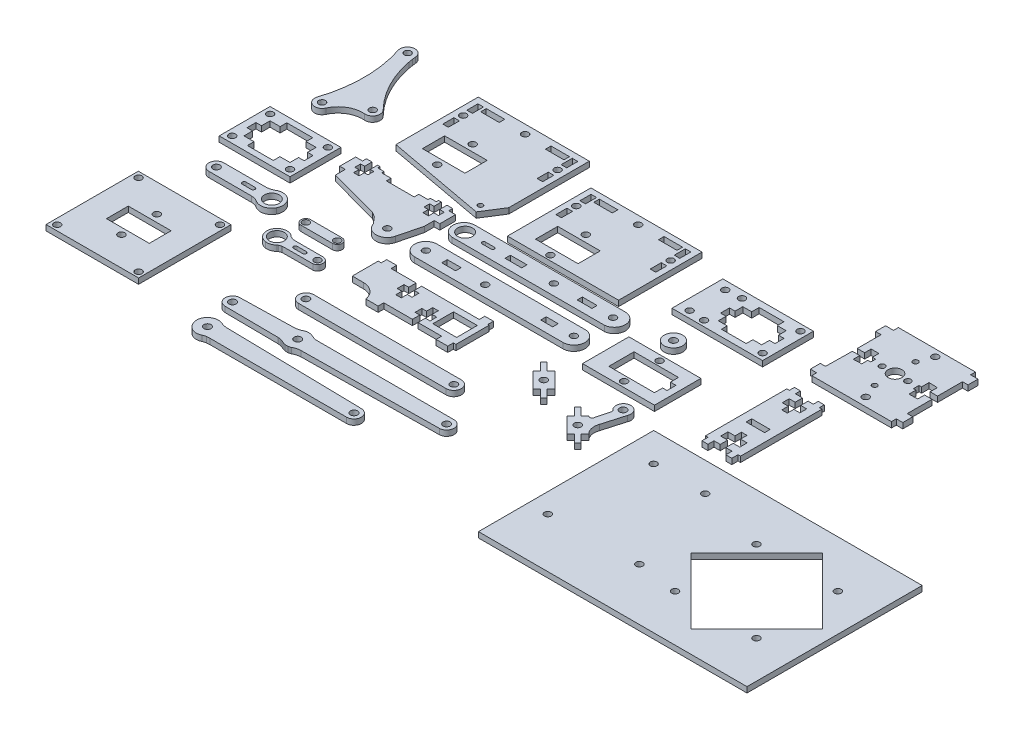
SolidWorks part; units mm, degrees
ref_plane "Front Plane" through (0, 0, 0) normal (0, 0, 1) x (1, 0, 0)
ref_plane "Top Plane" through (0, 0, 0) normal (0, 1, 0) x (1, 0, 0)
ref_plane "Right Plane" through (0, 0, 0) normal (1, 0, 0) x (0, 0, -1)
sketch "Sketch6" plane through (0, 0, -6.8736) normal (0, 1, 0) x (1, 0, 0)
  line L36 (172.3993, 17.524) -> (172.3993, 14.7799)
  line L37 (172.3993, 14.7799) -> (176.2794, 14.7799)
  line L38 (176.2794, 14.7799) -> (176.2794, 10.7799)
  line L39 (176.2794, 10.7799) -> (173.032, 10.7799)
  line L40 (173.032, 10.7799) -> (173.032, 7.063)
  line L41 (173.032, 7.063) -> (176.2794, 7.063)
  line L42 (176.2794, 7.063) -> (176.2794, 3.563)
  line L43 (176.2794, 3.563) -> (179.2794, 3.563)
  line L44 (179.2794, 3.563) -> (179.2794, 7.063)
  line L45 (179.2794, 7.063) -> (182.5439, 7.063)
  line L46 (182.5439, 7.063) -> (182.5439, 10.7799)
  line L47 (182.5439, 10.7799) -> (179.2794, 10.7799)
  line L48 (179.2794, 10.7799) -> (179.2794, 14.7799)
  line L49 (179.2794, 14.7799) -> (182.1277, 14.7799)
  line L50 (182.1277, 14.7799) -> (182.1277, 17.4216)
  line L54 (182.1277, -32.5784) -> (182.1277, -29.2201)
  line L55 (182.1277, -29.2201) -> (178.7635, -29.2201)
  line L56 (178.7635, -29.2201) -> (178.7635, -25.2201)
  line L57 (178.7635, -25.2201) -> (182.3404, -25.2201)
  line L58 (182.3404, -25.2201) -> (182.3404, -21.2526)
  line L59 (182.3404, -21.2526) -> (178.7635, -21.2526)
  line L60 (178.7635, -21.2526) -> (178.7635, -17.7526)
  line L61 (178.7635, -17.7526) -> (175.7635, -17.7526)
  line L62 (175.7635, -17.7526) -> (175.7635, -21.2526)
  line L63 (175.7635, -21.2526) -> (171.9828, -21.2526)
  line L64 (171.9828, -21.2526) -> (171.9828, -25.2201)
  line L65 (171.9828, -25.2201) -> (175.7635, -25.2201)
  line L66 (175.7635, -25.2201) -> (175.7635, -29.2201)
  line L67 (175.7635, -29.2201) -> (172.3993, -29.2201)
  line L68 (172.3993, -29.2201) -> (172.3993, -32.476)
  line L72 (172.2635, -8.7201) -> (182.2635, -8.7201)
  line L73 (182.2635, -8.7201) -> (182.2635, -11.7201)
  line L74 (182.2635, -11.7201) -> (172.2635, -11.7201)
  line L75 (172.2635, -11.7201) -> (172.2635, -8.7201)
  line L132 (186.7635, -29.2201) -> (185.3957, -29.2201)
  line L133 (185.3957, -29.2201) -> (185.3957, -32.5784)
  line L134 (167.7635, -29.2201) -> (169.1313, -29.2201)
  line L135 (169.1313, -29.2201) -> (169.1313, -32.476)
  line L136 (169.1313, 17.524) -> (169.1313, 14.7799)
  line L137 (169.1313, 14.7799) -> (167.7635, 14.7799)
  line L138 (185.3957, 17.4216) -> (185.3957, 14.7799)
  line L139 (185.3957, 14.7799) -> (186.7635, 14.7799)
  line L140 (167.7635, 14.7799) -> (167.7635, -29.2201)
  line L141 (169.1313, -32.476) -> (172.3993, -32.476)
  line L142 (182.1277, 17.4216) -> (185.3957, 17.4216)
  line L143 (186.7635, 14.7799) -> (186.7635, -29.2201)
  line L144 (185.3957, -32.5784) -> (182.1277, -32.5784)
  line L145 (169.1313, 17.524) -> (172.3993, 17.524)
  dimension "D6" = 1.3678
  dimension "D7" = 3.268
extrude "Boss-Extrude1" add sketch "Sketch6" along normal blind 3
sketch "Sketch12" plane through (0, 0, 0) normal (0, 1, 0) x (1, 0, 0)
  line L2 (6.7832, 13.9824) -> (88.1268, 13.9824)
  line L55 (6.1199, 2.1705) -> (88.7901, 2.1705)
  line L111 (69.455, 9.4201) -> (77.455, 9.4201)
  line L112 (69.455, 9.4201) -> (69.455, 6.6201)
  line L113 (69.455, 6.6201) -> (77.455, 6.6201)
  line L114 (77.455, 9.4201) -> (77.455, 6.6201)
  line L115 (30.455, 9.5201) -> (39.455, 9.5201)
  line L116 (30.455, 9.5201) -> (30.455, 6.6201)
  line L117 (30.455, 6.6201) -> (39.455, 6.6201)
  line L118 (39.455, 9.5201) -> (39.455, 6.6201)
  line L119 (17.455, 8.0462) -> (22.4277, 8.0462) construction
  line L120 (17.455, 8.9315) -> (22.4277, 8.9315)
  line L121 (17.455, 7.1609) -> (22.4277, 7.1609)
  arc A102 (6.7832, 13.9824) -> (6.1199, 2.1705) centre (6.7832, 8.0578) ccw
  arc A103 (88.1268, 13.9824) -> (88.7901, 2.1705) centre (88.1268, 8.0578) cw
  circle A104 centre (7.4627, 8.0462) radius 4
  circle A105 centre (87.455, 8.0201) radius 1.82
  circle A106 centre (55.455, 8.0201) radius 1.82
  arc A107 (17.455, 8.9315) -> (17.455, 7.1609) centre (17.455, 8.0462) ccw
  arc A108 (22.4277, 7.1609) -> (22.4277, 8.9315) centre (22.4277, 8.0462) ccw
  point P22 (19.9414, 8.0462)
  dimension "D1" = 3.64
  dimension "D3" = 3.64
  dimension "D4" = 8
extrude "Boss-Extrude3" add sketch "Sketch12" along normal blind 3 separate body
sketch "Sketch14" plane through (0, 0, 0) normal (0, 1, 0) x (1, 0, 0)
  line L0 (20.7129, 62.7973) -> (80.7867, 62.7973)
  line L1 (80.7867, 62.7973) -> (80.7867, 17.6847)
  line L2 (80.7867, 17.6847) -> (20.7129, 17.6847)
  line L3 (20.7129, 17.6847) -> (20.7129, 62.7973)
  line L4 (28.2425, 59.822) -> (38.2425, 59.822)
  line L5 (28.2425, 59.822) -> (28.2425, 56.822)
  line L6 (28.2425, 56.822) -> (38.2425, 56.822)
  line L7 (38.2425, 59.822) -> (38.2425, 56.822)
  line L8 (63.2425, 59.822) -> (73.2425, 59.822)
  line L9 (63.2425, 59.822) -> (63.2425, 56.822)
  line L10 (63.2425, 56.822) -> (73.2425, 56.822)
  line L11 (73.2425, 59.822) -> (73.2425, 56.822)
  line L12 (74.7425, 59.822) -> (77.7425, 59.822)
  line L13 (74.7425, 59.822) -> (74.7425, 53.822)
  line L14 (74.7425, 53.822) -> (77.7425, 53.822)
  line L15 (77.7425, 59.822) -> (77.7425, 53.822)
  line L16 (74.7425, 46.822) -> (77.7425, 46.822)
  line L17 (74.7425, 46.822) -> (74.7425, 40.822)
  line L18 (74.7425, 40.822) -> (77.7425, 40.822)
  line L19 (77.7425, 46.822) -> (77.7425, 40.822)
  line L20 (29.7425, 35.822) -> (52.7425, 35.822)
  line L21 (29.7425, 35.822) -> (29.7425, 23.822)
  line L22 (29.7425, 23.822) -> (52.7425, 23.822)
  line L23 (52.7425, 35.822) -> (52.7425, 23.822)
  line L24 (23.7425, 46.822) -> (26.7425, 46.822)
  line L25 (23.7425, 46.822) -> (23.7425, 40.822)
  line L26 (23.7425, 40.822) -> (26.7425, 40.822)
  line L27 (26.7425, 46.822) -> (26.7425, 40.822)
  line L28 (23.7425, 59.822) -> (26.7425, 59.822)
  line L29 (23.7425, 59.822) -> (23.7425, 53.822)
  line L30 (23.7425, 53.822) -> (26.7425, 53.822)
  line L31 (26.7425, 59.822) -> (26.7425, 53.822)
  circle A0 centre (50.7425, 58.322) radius 1.82
  circle A1 centre (41.2425, 39.4969) radius 1.82
  circle A2 centre (41.2425, 20.3569) radius 1.82
  circle A3 centre (76.2425, 50.322) radius 1.82
  circle A4 centre (25.2425, 50.322) radius 1.82
  dimension "D1" = 19.14
  dimension "D2" = 3.64
  dimension "D3" = 3.64
  dimension "D4" = 3.64
  dimension "D5" = 3.64
extrude "Boss-Extrude4" add sketch "Sketch14" along normal blind 3 separate body
sketch "Sketch18" plane through (0, 0, 0) normal (0, 1, 0) x (1, 0, 0)
  line L0 (-52.2788, 74.8705) -> (7.7767, 74.8705)
  line L1 (7.7767, 74.8705) -> (7.7767, 31.3788)
  line L2 (7.7767, 31.3788) -> (0.9291, 20.5522)
  line L3 (0.9291, 20.5522) -> (-52.2788, 30.361)
  line L4 (-52.2788, 30.361) -> (-52.2788, 74.8705)
  line L5 (-44.7078, 71.6303) -> (-34.7078, 71.6303)
  line L6 (-44.7078, 71.6303) -> (-44.7078, 68.6303)
  line L7 (-44.7078, 68.6303) -> (-34.7078, 68.6303)
  line L8 (-34.7078, 71.6303) -> (-34.7078, 68.6303)
  line L9 (-49.2078, 71.6303) -> (-46.2078, 71.6303)
  line L10 (-49.2078, 71.6303) -> (-49.2078, 65.6303)
  line L11 (-49.2078, 65.6303) -> (-46.2078, 65.6303)
  line L12 (-46.2078, 71.6303) -> (-46.2078, 65.6303)
  line L13 (-49.2078, 58.6303) -> (-46.2078, 58.6303)
  line L14 (-49.2078, 58.6303) -> (-49.2078, 52.6303)
  line L15 (-49.2078, 52.6303) -> (-46.2078, 52.6303)
  line L16 (-46.2078, 58.6303) -> (-46.2078, 52.6303)
  line L17 (-43.2078, 47.6303) -> (-20.2078, 47.6303)
  line L18 (-43.2078, 47.6303) -> (-43.2078, 35.6303)
  line L19 (-43.2078, 35.6303) -> (-20.2078, 35.6303)
  line L20 (-20.2078, 47.6303) -> (-20.2078, 35.6303)
  line L21 (-9.7078, 71.6303) -> (0.2922, 71.6303)
  line L22 (-9.7078, 71.6303) -> (-9.7078, 68.6303)
  line L23 (-9.7078, 68.6303) -> (0.2922, 68.6303)
  line L24 (0.2922, 71.6303) -> (0.2922, 68.6303)
  line L25 (1.7922, 71.6303) -> (4.7922, 71.6303)
  line L26 (1.7922, 71.6303) -> (1.7922, 65.6303)
  line L27 (1.7922, 65.6303) -> (4.7922, 65.6303)
  line L28 (4.7922, 71.6303) -> (4.7922, 65.6303)
  line L29 (1.7922, 58.6303) -> (4.7922, 58.6303)
  line L30 (1.7922, 58.6303) -> (1.7922, 52.6303)
  line L31 (1.7922, 52.6303) -> (4.7922, 52.6303)
  line L32 (4.7922, 58.6303) -> (4.7922, 52.6303)
  circle A0 centre (3.3054, 62.1514) radius 1.82
  circle A1 centre (-0.9558, 24.7244) radius 1.2998
  circle A2 centre (-31.7081, 32.1289) radius 1.82
  circle A3 centre (-31.6898, 51.2689) radius 1.82
  circle A4 centre (-47.7078, 62.1303) radius 1.82
  circle A5 centre (-22.2078, 70.1303) radius 1.82
  dimension "D1" = 3.64
  dimension "D2" = 19.14
sketch "Sketch20" plane through (0, 0, 0) normal (0, 1, 0) x (1, 0, 0)
  line L0 (-3.3445, 5.1376) -> (-6.3445, 5.1376)
  line L1 (-6.3445, -0.1855) -> (-9.5309, -12.7114)
  line L2 (-21.2346, -12.8672) -> (-24.3389, -9.2481)
  line L3 (-24.3389, -9.2481) -> (-27.0786, -7.6072)
  line L4 (-27.0786, -7.6072) -> (-54.3445, -0.2275)
  line L5 (-54.3445, -0.2275) -> (-54.3445, 5.0581)
  line L6 (-54.3445, 5.0581) -> (-57.3445, 5.0581)
  line L7 (-57.3445, 5.0581) -> (-57.3445, 13.6523)
  line L8 (-57.3445, 13.6523) -> (-53.6006, 13.6523)
  line L9 (-53.6006, 13.6523) -> (-53.6006, 15.7725)
  line L10 (-53.6006, 15.7725) -> (-50.5945, 15.7725)
  line L11 (-50.5945, 15.7725) -> (-50.5945, 11.7725)
  line L12 (-50.5945, 11.7725) -> (-52.7659, 11.7725)
  line L13 (-52.7659, 11.7725) -> (-52.7659, 8.6302)
  line L14 (-52.7659, 8.6302) -> (-50.5945, 8.6302)
  line L15 (-50.5945, 8.6302) -> (-50.5945, 5.7725)
  line L16 (-50.5945, 5.7725) -> (-47.5945, 5.7725)
  line L17 (-47.5945, 5.7725) -> (-47.5945, 8.6302)
  line L18 (-47.5945, 8.6302) -> (-45.6767, 8.6302)
  line L19 (-45.6767, 8.6302) -> (-45.6767, 11.7725)
  line L20 (-45.6767, 11.7725) -> (-47.5945, 11.7725)
  line L21 (-47.5945, 11.7725) -> (-47.5945, 15.7725)
  line L22 (-47.5945, 15.7725) -> (-46.26, 15.7725)
  line L23 (-46.26, 15.7725) -> (-46.26, 14.5225)
  line L24 (-46.26, 14.5225) -> (-42.8445, 14.5225)
  line L25 (-42.8445, 14.5225) -> (-42.8445, 13.2725)
  line L26 (-42.8445, 13.2725) -> (-37.8445, 13.2725)
  line L27 (-37.8445, 13.2725) -> (-37.8445, 10.7725)
  line L28 (-37.8445, 10.7725) -> (-22.8445, 10.7725)
  line L29 (-22.8445, 10.7725) -> (-22.8445, 13.2725)
  line L30 (-22.8445, 13.2725) -> (-17.8445, 13.2725)
  line L31 (-17.8445, 13.2725) -> (-17.8445, 14.5225)
  line L32 (-17.8445, 14.5225) -> (-14.6403, 14.5225)
  line L33 (-14.6403, 14.5225) -> (-14.6403, 15.7725)
  line L34 (-14.6403, 15.7725) -> (-13.0945, 15.7725)
  line L35 (-13.0945, 15.7725) -> (-13.0945, 11.7725)
  line L36 (-13.0945, 11.7725) -> (-15.4488, 11.7725)
  line L37 (-15.4488, 11.7725) -> (-15.4488, 8.6851)
  line L38 (-15.4488, 8.6851) -> (-13.0945, 8.6851)
  line L39 (-13.0945, 8.6851) -> (-13.0945, 5.7725)
  line L40 (-13.0945, 5.7725) -> (-10.0945, 5.7725)
  line L41 (-10.0945, 5.7725) -> (-10.0945, 8.6674)
  line L42 (-10.0945, 8.6674) -> (-7.5507, 8.6674)
  line L43 (-7.5507, 8.6674) -> (-7.5507, 11.7725)
  line L44 (-7.5507, 11.7725) -> (-10.0945, 11.7725)
  line L45 (-10.0945, 11.7725) -> (-10.0945, 15.7725)
  line L46 (-10.0945, 15.7725) -> (-7.0098, 15.7725)
  line L47 (-7.0098, 15.7725) -> (-7.0098, 13.684)
  line L48 (-7.0098, 13.684) -> (-3.3445, 13.6514)
  line L49 (-3.3445, 13.6514) -> (-3.3445, 5.1376)
  line L50 (-6.3445, 5.1376) -> (-6.3445, -0.1855)
  arc A0 (-9.5309, -12.7114) -> (-21.2346, -12.8672) centre (-15.4037, -11.2174) cw
  circle A1 centre (-15.3445, -11.2275) radius 1.82
  dimension "D1" = 3.64
sketch "Sketch22" plane through (0, 0, 0) normal (0, 1, 0) x (1, 0, 0)
  line L0 (-22.8304, -83.5062) -> (5.98, -82.8529)
  line L1 (18.5125, -82.749) -> (92.2578, -82.749)
  line L2 (92.3104, -90.7487) -> (18.5715, -91.7184)
  line L3 (6.0387, -91.7793) -> (-22.7778, -91.5049)
  arc A0 (5.98, -82.8529) -> (10.0623, -81.6918) centre (5.7889, -74.4239) ccw
  arc A1 (10.0623, -81.6918) -> (10.658, -81.4927) centre (10.8295, -82.9967) cw
  arc A2 (10.658, -81.4927) -> (11.2714, -81.3569) centre (10.3161, -78.495) ccw
  arc A3 (11.2714, -81.3569) -> (11.8955, -81.2861) centre (11.7502, -82.7912) cw
  arc A4 (11.8955, -81.2861) -> (12.5237, -81.2808) centre (12.1844, -78.2942) ccw
  arc A5 (12.5237, -81.2808) -> (13.1489, -81.3413) centre (12.6941, -82.7806) cw
  arc A6 (13.1489, -81.3413) -> (13.7644, -81.4668) centre (14.0525, -78.4818) ccw
  arc A7 (13.7644, -81.4668) -> (14.3634, -81.656) centre (13.6195, -82.9685) cw
  arc A8 (14.3634, -81.656) -> (14.9394, -81.9067) centre (15.8391, -79.0526) ccw
  arc A9 (14.9394, -81.9067) -> (15.6165, -82.2065) centre (13.9387, -85.0813) cw
  arc A10 (15.6165, -82.2065) -> (16.3185, -82.4423) centre (16.5367, -80.6298) ccw
  arc A11 (16.3185, -82.4423) -> (17.0393, -82.6122) centre (15.9213, -85.7415) cw
  arc A12 (17.0393, -82.6122) -> (17.7727, -82.7147) centre (17.6534, -80.8935) ccw
  arc A13 (17.7727, -82.7147) -> (18.5125, -82.749) centre (17.9898, -86.0281) cw
  arc A14 (92.2578, -82.749) -> (92.3104, -90.7487) centre (92.2578, -86.7491) cw
  arc A15 (18.5715, -91.7184) -> (14.4371, -92.8659) centre (18.6822, -100.1392) ccw
  arc A16 (14.4371, -92.8659) -> (13.8407, -93.0629) centre (13.6751, -91.5605) cw
  arc A17 (13.8407, -93.0629) -> (13.2269, -93.1965) centre (14.1702, -96.0538) ccw
  arc A18 (13.2269, -93.1965) -> (12.6025, -93.2652) centre (12.753, -91.7611) cw
  arc A19 (12.6025, -93.2652) -> (11.9743, -93.2682) centre (12.3027, -96.2616) ccw
  arc A20 (11.9743, -93.2682) -> (11.3493, -93.2055) centre (11.8094, -91.7654) cw
  arc A21 (11.3493, -93.2055) -> (10.7342, -93.0779) centre (10.4346, -96.0685) ccw
  arc A22 (10.7342, -93.0779) -> (10.1359, -92.8866) centre (10.8846, -91.5762) cw
  arc A23 (10.1359, -92.8866) -> (9.5608, -92.6338) centre (8.6482, -95.4904) ccw
  arc A24 (9.5608, -92.6338) -> (8.8936, -92.3352) centre (10.5595, -89.5075) cw
  arc A25 (8.8936, -92.3352) -> (8.202, -92.0988) centre (7.9736, -93.8967) ccw
  arc A26 (8.202, -92.0988) -> (7.4916, -91.9264) centre (8.615, -88.8472) cw
  arc A27 (7.4916, -91.9264) -> (6.7685, -91.8196) centre (6.8709, -93.6279) ccw
  arc A28 (6.7685, -91.8196) -> (6.0387, -91.7793) centre (6.5832, -88.5467) cw
  arc A29 (-22.7778, -91.5049) -> (-22.8304, -83.5062) centre (-22.7397, -87.5052) cw
  circle A30 centre (-22.7398, -87.5051) radius 1.925
  circle A31 centre (12.2595, -87.275) radius 1.925
  circle A32 centre (92.2578, -86.749) radius 1.925
  dimension "D1" = 3.85
  dimension "D2" = 3.85
sketch "Sketch23" plane through (0, 0, 0) normal (0, 1, 0) x (1, 0, 0)
  line L0 (62.0938, -102.6123) -> (-12.185, -101.1529)
  line L1 (62.0145, -110.6115) -> (-11.7091, -110.5993)
  arc A0 (-18.7722, -99.8781) -> (-23.9525, -106.2408) centre (-18.181, -105.6496) ccw
  arc A1 (-23.9525, -106.2408) -> (-20.8301, -111.1061) centre (-17.5842, -105.5884) ccw
  arc A2 (-20.8301, -111.1061) -> (-15.5368, -111.3053) centre (-17.9986, -106.2928) ccw
  arc A3 (-15.5368, -111.3053) -> (-13.6142, -110.7239) centre (-12.8064, -116.8649) cw
  arc A4 (-13.6142, -110.7239) -> (-11.7091, -110.5993) centre (-11.7115, -125.1879) cw
  arc A5 (-18.7722, -99.8781) -> (-14.8108, -100.6548) centre (-18.0664, -106.7687) cw
  arc A6 (-14.8108, -100.6548) -> (-13.5188, -101.0143) centre (-13.353, -97.9172) ccw
  arc A7 (-13.5188, -101.0143) -> (-12.185, -101.1529) centre (-14.2348, -114.3916) cw
  arc A8 (62.0938, -102.6123) -> (62.0145, -110.6115) centre (62.0152, -106.6115) cw
  circle A9 centre (62.0152, -106.6115) radius 1.925
  circle A10 centre (-17.9809, -105.8257) radius 1.925
  dimension "D1" = 3.85
  dimension "D2" = 3.85
sketch "Sketch24" plane through (0, 0, 0) normal (0, 1, 0) x (1, 0, 0)
  line L0 (-90.2893, -24.7085) -> (-67.8284, -24.7085)
  line L1 (-90.2954, -32.7085) -> (-67.194, -32.744)
  line L2 (-75.2787, -28.7329) -> (-70.3703, -28.7329) construction
  line L3 (-75.2787, -27.7198) -> (-70.3703, -27.7198)
  line L4 (-75.2787, -29.7461) -> (-70.3703, -29.7461)
  arc A0 (-67.8284, -24.7085) -> (-62.5705, -23.1591) centre (-67.8284, -15.0125) ccw
  arc A1 (-62.5705, -23.1591) -> (-54.9836, -31.523) centre (-60.3229, -28.7434) cw
  arc A2 (-54.9836, -31.523) -> (-63.9473, -33.5823) centre (-60.343, -28.7329) cw
  arc A3 (-67.194, -32.744) -> (-63.9473, -33.5823) centre (-67.2043, -39.4905) cw
  arc A4 (-75.2787, -27.7198) -> (-75.2787, -29.7461) centre (-75.2787, -28.7329) ccw
  arc A5 (-70.3703, -29.7461) -> (-70.3703, -27.7198) centre (-70.3703, -28.7329) ccw
  circle A6 centre (-90.2893, -28.7085) radius 1.925
  circle A7 centre (-60.2893, -28.7085) radius 4
  arc A8 (-90.2954, -32.7085) -> (-90.2893, -24.7085) centre (-90.2893, -28.7085) cw
  point P13 (-72.8245, -28.7329)
  dimension "D1" = 3.85
  dimension "D2" = 8
sketch "Sketch26" plane through (0, 0, 0) normal (0, 1, 0) x (1, 0, 0)
  line L0 (-87.7528, 74.718) -> (-87.4104, 72.6313)
  line L1 (-87.7528, 74.718) -> (-88.0164, 76.816)
  arc A0 (-88.0164, 76.816) -> (-95.8236, 75.1147) centre (-92.0067, 76.3629) ccw
  arc A1 (-95.8236, 75.1147) -> (-95.7872, 31.4073) centre (-162.8228, 53.2052) cw
  arc A2 (-95.7872, 31.4073) -> (-88.3346, 28.5226) centre (-91.9816, 30.1698) ccw
  arc A3 (-88.3346, 28.5226) -> (-75.123, 36.3095) centre (-76.205, 23.044) cw
  arc A4 (-75.123, 36.3095) -> (-71.9331, 43.1193) centre (-74.7969, 40.3087) ccw
  arc A5 (-71.9331, 43.1193) -> (-87.4104, 72.6313) centre (-30.7636, 83.5248) cw
  circle A6 centre (-74.764, 40.2933) radius 1.82
  circle A7 centre (-91.9939, 30.1381) radius 1.82
  circle A8 centre (-91.9939, 76.3923) radius 1.82
  dimension "D1" = 3.64
  dimension "D2" = 3.64
  dimension "D3" = 3.64
sketch "Sketch27" plane through (0, 0, 0) normal (0, 1, 0) x (1, 0, 0)
  line L0 (-91.9831, 11.0737) -> (-77.9831, 11.0737)
  line L1 (-104.1231, 14.1616) -> (-65.8431, 14.1616)
  line L2 (-104.1231, 14.1616) -> (-104.1231, -13.3284)
  line L3 (-104.1231, -13.3284) -> (-65.8431, -13.3284)
  line L4 (-65.8431, 14.1616) -> (-65.8431, -13.3284)
  line L5 (-77.9831, 11.0737) -> (-77.9831, 7.4737)
  line L6 (-77.9831, 7.4737) -> (-72.5331, 7.4737)
  line L7 (-72.5331, 7.4737) -> (-72.5331, 2.8437)
  line L8 (-69.5331, 2.8437) -> (-69.5331, -2.0063)
  line L9 (-69.5331, -2.0063) -> (-72.5331, -2.0063)
  line L10 (-72.5331, -2.0063) -> (-72.5331, -6.6363)
  line L11 (-72.5331, -6.6363) -> (-77.9831, -6.6363)
  line L12 (-77.9831, -6.6363) -> (-77.9831, -10.2363)
  line L13 (-77.9831, -10.2363) -> (-91.9831, -10.2363)
  line L14 (-91.9831, -10.2363) -> (-91.9831, -6.6384)
  line L15 (-91.9831, -6.6384) -> (-97.4331, -6.6384)
  line L16 (-97.4331, -6.6384) -> (-97.4331, -2.0084)
  line L17 (-97.4331, -2.0084) -> (-100.4331, -2.0084)
  line L18 (-100.4331, -2.0084) -> (-100.4331, 2.8416)
  line L19 (-100.4331, 2.8416) -> (-97.4331, 2.8416)
  line L20 (-97.4331, 2.8416) -> (-97.4331, 7.4716)
  line L21 (-97.4331, 7.4716) -> (-91.9831, 7.4716)
  line L22 (-91.9831, 7.4716) -> (-91.9831, 11.0737)
  line L23 (-72.5331, 2.8437) -> (-69.5331, 2.8437)
  circle A0 centre (-100.6231, 10.6616) radius 1.82
  circle A1 centre (-100.6231, -9.8284) radius 1.82
  circle A2 centre (-69.3431, -9.8263) radius 1.82
  circle A3 centre (-69.3431, 10.6616) radius 1.82
  dimension "D1" = 3.64
  dimension "D2" = 14
  dimension "D3" = 3.6
  dimension "D4" = 3.6
  dimension "D5" = 4.85
  dimension "D6" = 4.63
  dimension "D7" = 3.19
  dimension "D8" = 3.19
  dimension "D9" = 3.19
  dimension "D10" = 5.45
  dimension "D11" = 3
  dimension "D12" = 3.19
  dimension "D13" = 3.19
  dimension "D14" = 3.19
  dimension "D15" = 3.5
  dimension "D16" = 3.5
  dimension "D17" = 3.5
sketch "Sketch28" plane through (0, 0, 0) normal (0, 1, 0) x (1, 0, 0)
  line L0 (109.0997, -2.2732) -> (133.1497, -2.2732)
  line L1 (100.7124, 3.3321) -> (139.6281, 3.3321)
  line L2 (100.7124, 3.3321) -> (100.7124, -21.7433)
  line L3 (100.7124, -21.7433) -> (139.6281, -21.7433)
  line L4 (139.6281, 3.3321) -> (139.6281, -21.7433)
  line L5 (133.1497, -2.2732) -> (133.1497, -6.6732)
  line L6 (133.1497, -6.6732) -> (136.1497, -6.6732)
  line L7 (136.1497, -6.6732) -> (136.1497, -11.5232)
  line L8 (136.1497, -11.5232) -> (133.7949, -11.5232)
  line L9 (133.7949, -11.5232) -> (133.7949, -15.9232)
  line L10 (133.7949, -15.9232) -> (109.0997, -15.9232)
  line L11 (109.0997, -15.9232) -> (109.0997, -2.2732)
  circle A0 centre (120.2396, 0.384) radius 1.82
  circle A1 centre (120.2396, -18.756) radius 1.82
  dimension "D1" = 3.64
  dimension "D2" = 3.64
  dimension "D3" = 3
  dimension "D4" = 24.05
  dimension "D5" = 4.85
  dimension "D6" = 4.4
  dimension "D7" = 19.14
sketch "Sketch29" plane through (0, 0, 0) normal (0, 1, 0) x (1, 0, 0)
  line L0 (122.1756, 52.3026) -> (135.5756, 52.3026)
  line L1 (98.979, 55.8405) -> (147.9656, 55.8405)
  line L2 (98.979, 55.8405) -> (98.979, 28.3505)
  line L3 (98.979, 28.3505) -> (147.9656, 28.3505)
  line L4 (147.9656, 55.8405) -> (147.9656, 28.3505)
  line L5 (135.5756, 52.3026) -> (135.5756, 48.7026)
  line L6 (135.5756, 48.7026) -> (140.3756, 48.7026)
  line L7 (140.3756, 48.7026) -> (140.3756, 44.5226)
  line L8 (143.3756, 44.5226) -> (143.3756, 39.6726)
  line L9 (143.3756, 39.6726) -> (140.3756, 39.6726)
  line L10 (140.3756, 39.6726) -> (140.3756, 35.4926)
  line L11 (140.3756, 35.4926) -> (135.5756, 35.4926)
  line L12 (135.5756, 35.4926) -> (135.5756, 31.8926)
  line L13 (135.5756, 31.8926) -> (122.1756, 31.8926)
  line L14 (122.1756, 31.8926) -> (122.1756, 35.0385)
  line L15 (122.1756, 35.0385) -> (117.3756, 35.0385)
  line L16 (117.3756, 35.0385) -> (117.3756, 39.2185)
  line L17 (117.3756, 39.2185) -> (114.3756, 39.2185)
  line L18 (114.3756, 39.2185) -> (114.3756, 44.0726)
  line L19 (114.3756, 44.0726) -> (117.3756, 44.0726)
  line L20 (117.3756, 44.0726) -> (117.3756, 48.2526)
  line L21 (117.3756, 48.2526) -> (122.1756, 48.2526)
  line L22 (122.1756, 48.2526) -> (122.1756, 52.3026)
  line L23 (140.3756, 44.5226) -> (143.3756, 44.5226)
  circle A0 centre (113.2856, 51.8905) radius 1.82
  circle A1 centre (113.2856, 31.4005) radius 1.82
  circle A2 centre (144.4656, 31.8547) radius 1.82
  circle A3 centre (144.4656, 52.3405) radius 1.82
  circle A4 centre (104.8061, 51.3081) radius 1.82
  circle A5 centre (104.8304, 32.0181) radius 1.82
  point P72 (0, 0)
  point P73 (107.068, 31.8505)
  dimension "D1" = 3.64
  dimension "D35" = 3.6379
  dimension "D2" = 13.4
  dimension "D3" = 3.6
  dimension "D4" = 3.6
  dimension "D5" = 4.85
  dimension "D6" = 4.18
  dimension "D7" = 4.09
  dimension "D8" = 3.6379
  dimension "D9" = 4.09
  dimension "D10" = 4.8
  dimension "D11" = 3
  dimension "D12" = 4.09
  dimension "D13" = 3.6379
  dimension "D14" = 4.09
  dimension "D15" = 3.5
  dimension "D16" = 3.5
  dimension "D17" = 19.29
  dimension "D36" = 3.6379
  dimension "D37" = 3.6379
sketch "Sketch30" plane through (0, 0, 0) normal (0, 1, 0) x (1, 0, 0)
  line L0 (17.989, -28.9872) -> (4.4448, -28.9872)
  line L1 (11.9231, -50.0571) -> (18.5165, -50.0571)
  line L2 (18.5165, -50.0571) -> (18.5165, -46.9872)
  line L3 (18.5165, -46.9872) -> (33.989, -46.9872)
  line L4 (33.989, -46.9872) -> (33.989, -42.9872)
  line L5 (33.989, -42.9872) -> (31.4392, -42.9872)
  line L6 (31.4392, -42.9872) -> (31.4392, -39.3422)
  line L7 (31.4392, -39.3422) -> (33.989, -39.3422)
  line L8 (33.989, -39.3422) -> (33.989, -35.9872)
  line L9 (33.989, -35.9872) -> (36.989, -35.9872)
  line L10 (36.989, -35.9872) -> (36.989, -39.3774)
  line L11 (36.989, -39.3774) -> (39.5388, -39.3774)
  line L12 (39.5388, -39.3774) -> (39.5388, -42.9872)
  line L13 (39.5388, -42.9872) -> (36.989, -42.9872)
  line L14 (36.989, -42.9872) -> (36.989, -46.9872)
  line L15 (36.989, -46.9872) -> (49.8067, -46.9872)
  line L16 (49.8067, -46.9872) -> (49.8067, -49.9872)
  line L17 (52.1127, -25.9872) -> (52.1127, -28.9872)
  line L18 (52.1127, -28.9872) -> (20.989, -28.9872)
  line L19 (20.989, -28.9872) -> (20.989, -32.9872)
  line L20 (20.989, -32.9872) -> (23.539, -32.9872)
  line L21 (23.539, -32.9872) -> (23.539, -36.7505)
  line L22 (23.539, -36.7505) -> (20.989, -36.7505)
  line L23 (20.989, -36.7505) -> (20.989, -39.9872)
  line L24 (20.989, -39.9872) -> (17.989, -39.9872)
  line L25 (17.989, -39.9872) -> (17.989, -36.6921)
  line L26 (17.989, -36.6921) -> (15.439, -36.6921)
  line L27 (15.439, -36.6921) -> (15.439, -32.9872)
  line L28 (15.439, -32.9872) -> (17.989, -32.9872)
  line L29 (17.989, -32.9872) -> (17.989, -28.9872)
  line L30 (4.4448, -28.9872) -> (4.4448, -25.9872)
  line L31 (41.6011, -32.3441) -> (54.4301, -32.3441)
  line L32 (41.6011, -32.3441) -> (41.6011, -43.5339)
  line L33 (41.6011, -43.5339) -> (54.4301, -43.5339)
  line L34 (54.4301, -32.3441) -> (54.4301, -43.5339)
  line L35 (-2.511, -42.9872) -> (3.489, -42.9872)
  line L36 (-0.8977, -25.9872) -> (-0.8977, -28.9872)
  line L37 (-0.8977, -28.9872) -> (-2.511, -28.9872)
  line L38 (56.0898, -49.9872) -> (56.0898, -46.9872)
  line L39 (56.0898, -46.9872) -> (57.489, -46.9872)
  line L40 (56.7962, -25.9872) -> (56.7962, -28.9872)
  line L41 (56.7962, -28.9872) -> (57.489, -28.9872)
  line L42 (57.489, -28.9872) -> (57.489, -46.9872)
  line L43 (56.0898, -49.9872) -> (49.8067, -49.9872)
  line L44 (56.7962, -25.9872) -> (52.1127, -25.9872)
  line L45 (-0.8977, -25.9872) -> (4.4448, -25.9872)
  line L46 (-2.511, -42.9872) -> (-2.511, -28.9872)
  arc A0 (3.489, -42.9872) -> (11.9231, -50.0571) centre (3.489, -51.5529) cw
  dimension "D1" = 3.645
  dimension "D2" = 2.5498
  dimension "D3" = 2.55
  dimension "D4" = 2.55
  dimension "D5" = 2.55
  dimension "D6" = 2.55
sketch "Sketch31" plane through (0, 0, 0) normal (0, 1, 0) x (1, 0, 0)
  line L0 (-40.1799, -27.8411) -> (-23.1799, -27.8411)
  line L1 (-23.1799, -33.0411) -> (-40.1799, -33.0411)
  arc A0 (-23.1799, -27.8411) -> (-23.1799, -33.0411) centre (-23.1799, -30.4411) cw
  arc A1 (-40.1799, -33.0411) -> (-40.1799, -27.8411) centre (-40.1799, -30.4411) cw
  circle A2 centre (-40.1799, -30.4411) radius 1.82
  circle A3 centre (-23.1799, -30.4411) radius 1.82
  dimension "D1" = 3.64
  dimension "D2" = 3.64
  dimension "D3" = 2.6
  dimension "D4" = 2.6
  dimension "D5" = 2.6
sketch "Sketch32" plane through (0, 0, 0) normal (0, 1, 0) x (1, 0, 0)
  line L0 (-19.3691, -41.9276) -> (-34.5684, -41.9276)
  line L1 (-18.8998, -47.8907) -> (-35.1542, -47.962)
  line L2 (-35.1542, -47.962) -> (-35.7319, -48.0649)
  line L3 (-31.4441, -44.9276) -> (-26.3849, -44.9276) construction
  line L4 (-31.4441, -43.9544) -> (-26.3849, -43.9544)
  line L5 (-31.4441, -45.9008) -> (-26.3849, -45.9008)
  arc A0 (-34.5684, -41.9276) -> (-38.333, -40.3416) centre (-34.5684, -36.6667) cw
  arc A1 (-38.333, -40.3416) -> (-42.1025, -50.3785) centre (-41.3099, -44.9499) ccw
  arc A2 (-42.1025, -50.3785) -> (-37.3382, -48.7649) centre (-41.3026, -44.9) ccw
  arc A3 (-37.3382, -48.7649) -> (-36.8315, -48.4691) centre (-36.5499, -49.5334) cw
  arc A4 (-36.8315, -48.4691) -> (-35.7319, -48.0649) centre (-38.4338, -42.4122) ccw
  arc A5 (-19.3691, -41.9276) -> (-18.8998, -47.8907) centre (-19.3691, -44.9276) cw
  arc A6 (-31.4441, -43.9544) -> (-31.4441, -45.9008) centre (-31.4441, -44.9276) ccw
  arc A7 (-26.3849, -45.9008) -> (-26.3849, -43.9544) centre (-26.3849, -44.9276) ccw
  circle A8 centre (-41.3691, -44.9276) radius 4
  circle A9 centre (-19.3691, -44.9276) radius 1.82
  point P17 (-28.9145, -44.9276)
  dimension "D1" = 3.64
sketch "Sketch33" plane through (0, 0, 0) normal (0, 1, 0) x (1, 0, 0)
  line L0 (-4.2145, -66.2122) -> (75.574, -66.2122) construction
  line L1 (-4.2145, -62.1261) -> (75.574, -62.1261)
  line L2 (-4.2145, -70.2983) -> (75.574, -70.2983)
  arc A0 (-4.2145, -62.1261) -> (-4.2145, -70.2983) centre (-4.2145, -66.2122) ccw
  arc A1 (75.574, -70.2983) -> (75.574, -62.1261) centre (75.574, -66.2122) ccw
  circle A2 centre (-4.3278, -66.2456) radius 1.87
  circle A3 centre (75.6722, -66.2456) radius 1.87
  point P2 (35.6798, -66.2122)
  dimension "D1" = 3.74
  dimension "D2" = 3.74
sketch "Sketch34" plane through (0, 0, 0) normal (0, 1, 0) x (1, 0, 0)
  line L0 (85.46, -5.1233) -> (5.46, -5.1233)
  line L1 (5.3693, -17.1401) -> (85.46, -17.1233)
  line L2 (85.46, -17.1401) -> (85.46, -17.1233)
  line L3 (15.46, -9.6233) -> (22.96, -9.6233)
  line L4 (15.46, -9.6233) -> (15.46, -12.6233)
  line L5 (15.46, -12.6233) -> (22.96, -12.6233)
  line L6 (22.96, -9.6233) -> (22.96, -12.6233)
  line L7 (68.9695, -9.6233) -> (75.46, -9.6233)
  line L8 (68.9695, -9.6233) -> (68.9695, -12.6233)
  line L9 (68.9695, -12.6233) -> (75.46, -12.6233)
  line L10 (75.46, -9.6233) -> (75.46, -12.6233)
  arc A0 (5.46, -5.1233) -> (5.3693, -17.1401) centre (5.4147, -11.1317) ccw
  arc A1 (85.46, -5.1233) -> (85.46, -17.1401) centre (85.46, -11.1317) cw
  circle A2 centre (85.46, -11.1233) radius 1.82
  circle A3 centre (37.46, -11.1233) radius 1.82
  circle A4 centre (5.46, -11.1233) radius 1.82
  dimension "D1" = 3.64
  dimension "D2" = 3.64
  dimension "D3" = 3.64
sketch "Sketch35" plane through (0, 0, 0) normal (0, 1, 0) x (1, 0, 0)
  circle A0 centre (114.4508, 13.6733) radius 1.925
  circle A1 centre (114.4508, 13.6733) radius 5
  dimension "D1" = 3.85
sketch "Sketch36" plane through (0, 0, 0) normal (0, 1, 0) x (1, 0, 0)
  line L0 (96.6735, -32.7093) -> (105.1588, -41.1946)
  line L1 (105.1588, -41.1946) -> (103.0375, -43.3159)
  line L2 (103.0375, -43.3159) -> (107.2801, -47.5586)
  line L3 (107.2801, -47.5586) -> (105.583, -49.2556)
  line L4 (105.583, -49.2556) -> (101.3404, -45.013)
  line L5 (101.3404, -45.013) -> (99.2191, -47.1343)
  line L6 (99.2191, -47.1343) -> (90.7338, -38.6491)
  line L7 (90.7338, -38.6491) -> (92.8551, -36.5277)
  line L8 (92.8551, -36.5277) -> (88.6125, -32.2851)
  line L9 (88.6125, -32.2851) -> (90.3095, -30.588)
  line L10 (90.3095, -30.588) -> (94.5522, -34.8307)
  line L11 (94.5522, -34.8307) -> (96.6735, -32.7093)
  circle A0 centre (97.9463, -39.9218) radius 1.82
  dimension "D1" = 3.64
sketch "Sketch37" plane through (0, 0, 0) normal (0, 1, 0) x (1, 0, 0)
  line L0 (135.4169, -53.0651) -> (133.2956, -55.1864)
  line L1 (133.2956, -55.1864) -> (137.5382, -59.4291)
  line L2 (137.5382, -59.4291) -> (135.8412, -61.1261)
  line L3 (135.8412, -61.1261) -> (131.5985, -56.8835)
  line L4 (131.5985, -56.8835) -> (129.4772, -59.0048)
  line L5 (129.4772, -59.0048) -> (120.9919, -50.5195)
  line L6 (120.9919, -50.5195) -> (123.1132, -48.3982)
  line L7 (123.1132, -48.3982) -> (118.8706, -44.1556)
  line L8 (118.8706, -44.1556) -> (120.5677, -42.4585)
  line L9 (120.5677, -42.4585) -> (124.8103, -46.7012)
  line L10 (124.8103, -46.7012) -> (126.9316, -44.5798)
  line L11 (129.1898, -43.6445) -> (131.0313, -36.7977)
  line L12 (133.7199, -45.6405) -> (137.1051, -33.9217)
  line L13 (131.0313, -36.7977) -> (131.0313, -35.5609)
  arc A0 (126.9316, -44.5798) -> (129.1898, -43.6445) centre (127.867, -43.6445) ccw
  arc A1 (135.4169, -53.0651) -> (133.7199, -45.6405) centre (140.4805, -48.0015) cw
  circle A2 centre (133.3808, -32.4738) radius 1.925
  arc A3 (137.1051, -33.9217) -> (131.0313, -35.5609) centre (133.4056, -32.2861) ccw
  circle A4 centre (128.2044, -51.7923) radius 1.8201
  dimension "D1" = 3.6402
  dimension "D2" = 3.85
sketch "Sketch38" plane through (0, 0, 0) normal (0, 1, 0) x (1, 0, 0)
  line L0 (214.8986, 72.4925) -> (211.8986, 72.4925)
  line L1 (211.8986, 72.4925) -> (211.8986, 59.0158)
  line L2 (211.8986, 59.0158) -> (207.8986, 59.0158)
  line L3 (207.8986, 59.0158) -> (207.8986, 62.9131)
  line L4 (207.8986, 62.9131) -> (203.2662, 63.0537)
  line L5 (203.2662, 63.0537) -> (203.2662, 59.0158)
  line L6 (203.2662, 59.0158) -> (201.8986, 59.0158)
  line L7 (201.8986, 59.0158) -> (201.8986, 56.0158)
  line L8 (201.8986, 56.0158) -> (203.2651, 56.0158)
  line L9 (203.2651, 56.0158) -> (203.2651, 52.2449)
  line L10 (203.2651, 52.2449) -> (207.8986, 52.2911)
  line L11 (207.8986, 52.2911) -> (207.8986, 56.0158)
  line L12 (207.8986, 56.0158) -> (211.8986, 56.0158)
  line L13 (211.8986, 56.0158) -> (211.8986, 42.6429)
  line L14 (211.8986, 42.6429) -> (214.8986, 42.6429)
  line L15 (164.8986, 42.6429) -> (167.6736, 42.6429)
  line L16 (167.8986, 56.962) -> (171.8986, 56.962)
  line L17 (171.8986, 56.962) -> (171.8986, 53.4656)
  line L18 (171.8986, 53.4656) -> (176.3141, 53.6437)
  line L19 (176.3141, 53.6437) -> (176.3141, 56.962)
  line L20 (176.3141, 56.962) -> (177.8986, 56.962)
  line L21 (177.8986, 56.962) -> (177.8986, 59.6133)
  line L22 (177.8986, 59.6133) -> (176.1034, 59.6133)
  line L23 (176.1034, 59.6133) -> (176.1034, 63.1125)
  line L24 (176.1034, 63.1125) -> (171.8986, 63.1125)
  line L25 (171.8986, 63.1125) -> (171.8986, 59.6133)
  line L26 (171.8986, 59.6133) -> (167.8986, 59.6133)
  line L27 (167.8986, 59.6133) -> (167.8986, 72.4925)
  line L28 (167.8986, 72.4925) -> (164.8986, 72.4925)
  line L29 (167.6736, 42.6429) -> (167.8986, 56.962)
  line L30 (214.8986, 37.2429) -> (211.4066, 37.2429)
  line L31 (211.4066, 37.2429) -> (211.4066, 34.6032)
  line L32 (164.8986, 37.2429) -> (168.3401, 37.2429)
  line L33 (168.3401, 37.2429) -> (168.3401, 34.6032)
  line L34 (214.8986, 37.2429) -> (214.8986, 42.6429)
  line L35 (211.4066, 34.6032) -> (168.3401, 34.6032)
  line L36 (164.8986, 37.2429) -> (164.8986, 42.6429)
  line L37 (210.8826, 80.5322) -> (210.8826, 77.8925)
  line L38 (210.8826, 77.8925) -> (214.8986, 77.8925)
  line L39 (164.8986, 77.8925) -> (169.2475, 77.8925)
  line L40 (169.2475, 77.8925) -> (169.2475, 80.5322)
  line L41 (169.2475, 80.5322) -> (210.8826, 80.5322)
  line L42 (164.8986, 77.8925) -> (164.8986, 72.4925)
  line L43 (214.8986, 72.4925) -> (214.8986, 77.8925)
  circle A0 centre (189.8986, 58.0322) radius 3.75
  circle A1 centre (182.8986, 58.0322) radius 1.5333
  circle A2 centre (189.889, 69.1146) radius 1.4239
  circle A3 centre (196.8493, 58.0203) radius 1.6482
  circle A4 centre (192.8986, 76.7822) radius 1.82
  circle A5 centre (189.8986, 47.0381) radius 1.3524
  circle A6 centre (192.885, 39.1928) radius 1.82
  dimension "D6" = 3.64
  dimension "D7" = 3.64
  dimension "D1" = 5.4
  dimension "D2" = 5.4
  dimension "D3" = 5.4
  dimension "D4" = 5.4
  dimension "D5" = 2.6397
extrude "Boss-Extrude5" add sketch "Sketch18" along normal blind 3 separate body
extrude "Boss-Extrude6" add sketch "Sketch38" along normal blind 3 separate body
extrude "Boss-Extrude7" add sketch "Sketch37" along normal blind 3 separate body
extrude "Boss-Extrude8" add sketch "Sketch36" along normal blind 3 separate body
extrude "Boss-Extrude9" add sketch "Sketch35" along normal blind 3 separate body
extrude "Boss-Extrude10" add sketch "Sketch34" along normal blind 3 separate body
extrude "Boss-Extrude11" add sketch "Sketch33" along normal blind 3 separate body
extrude "Boss-Extrude12" add sketch "Sketch32" along normal blind 3 separate body
extrude "Boss-Extrude13" add sketch "Sketch31" along normal blind 3 separate body
extrude "Boss-Extrude14" add sketch "Sketch30" along normal blind 3 separate body
extrude "Boss-Extrude15" add sketch "Sketch29" along normal blind 3 separate body
extrude "Boss-Extrude16" add sketch "Sketch28" along normal blind 3 separate body
extrude "Boss-Extrude17" add sketch "Sketch27" along normal blind 3 separate body
extrude "Boss-Extrude18" add sketch "Sketch26" along normal blind 3 separate body
extrude "Boss-Extrude19" add sketch "Sketch24" along normal blind 3 separate body
extrude "Boss-Extrude20" add sketch "Sketch23" along normal blind 3 separate body
extrude "Boss-Extrude21" add sketch "Sketch22" along normal blind 3 separate body
extrude "Boss-Extrude22" add sketch "Sketch20" along normal blind 3 separate body
sketch "Sketch41" plane through (0, 0, 0) normal (0, 1, 0) x (1, 0, 0)
  line L0 (218.7805, -81.1114) -> (254.3702, -116.7011)
  line L1 (151.2617, -33.8089) -> (296.4281, -33.8089)
  line L2 (151.2617, -33.8089) -> (151.2617, -128.5401)
  line L3 (151.2617, -128.5401) -> (296.4281, -128.5401)
  line L4 (296.4281, -33.8089) -> (296.4281, -128.5401)
  line L5 (254.3702, -116.7011) -> (289.8339, -81.2374)
  line L6 (289.8339, -81.2374) -> (254.2442, -45.6477)
  line L7 (254.2442, -45.6477) -> (218.7805, -81.1114)
  circle A0 centre (232.313, -59.3089) radius 1.82
  circle A1 centre (194.813, -49.5089) radius 1.82
  circle A2 centre (166.913, -49.5089) radius 1.82
  circle A3 centre (161.813, -101.6089) radius 1.82
  circle A4 centre (210.013, -100.3089) radius 1.82
  circle A5 centre (232.313, -103.3089) radius 1.82
  circle A6 centre (276.313, -103.3089) radius 1.82
  circle A7 centre (276.313, -59.3089) radius 1.82
  dimension "D1" = 3.64
extrude "Boss-Extrude23" add sketch "Sketch41" along normal blind 3 separate body
sketch "Sketch42" plane through (0, 0, 0) normal (0, 1, 0) x (1, 0, 0)
  line L0 (-109.4446, -51.7385) -> (-59.3919, -51.7385)
  line L1 (-109.4446, -51.7385) -> (-109.4446, -101.6556)
  line L2 (-109.4446, -101.6556) -> (-59.3919, -101.6556)
  line L3 (-59.3919, -51.7385) -> (-59.3919, -101.6556)
  line L4 (-95.8417, -82.5662) -> (-72.6942, -82.5662)
  line L5 (-95.8417, -82.5662) -> (-95.8417, -70.7669)
  line L6 (-95.8417, -70.7669) -> (-72.6942, -70.7669)
  line L7 (-72.6942, -82.5662) -> (-72.6942, -70.7669)
  circle A0 centre (-106.3103, -54.7462) radius 1.82
  circle A1 centre (-84.3064, -66.8836) radius 1.82
  circle A2 centre (-62.3037, -54.735) radius 1.82
  circle A3 centre (-84.3093, -86.0236) radius 1.82
  circle A4 centre (-62.3053, -98.732) radius 1.82
  circle A5 centre (-106.3086, -98.7412) radius 1.82
  dimension "D1" = 19.14
  dimension "D2" = 3.64
extrude "Boss-Extrude24" add sketch "Sketch42" along normal blind 3 separate body
